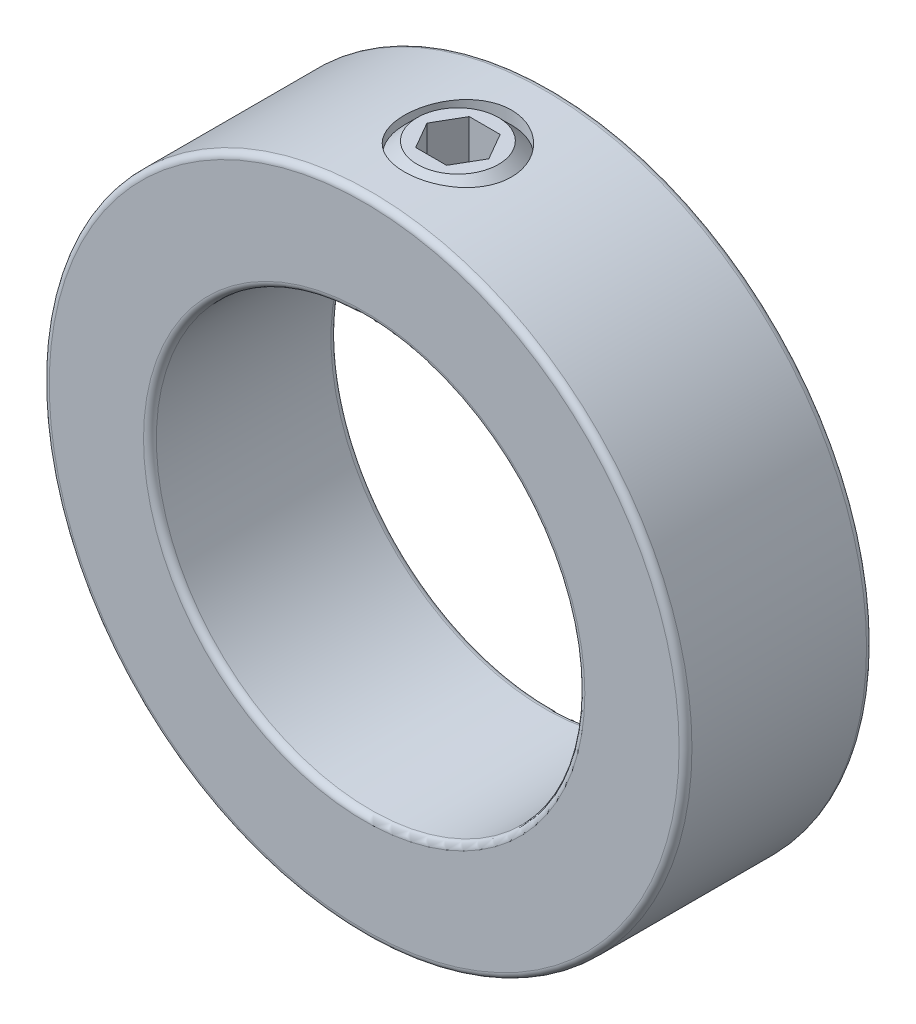
SolidWorks part; units mm, degrees
ref_plane "Front Plane" through (0, 0, 0) normal (0, 0, 1) x (1, 0, 0)
ref_plane "Top Plane" through (0, 0, 0) normal (0, 1, 0) x (1, 0, 0)
ref_plane "Right Plane" through (0, 0, 0) normal (1, 0, 0) x (0, 0, -1)
sketch "Sketch1" plane through (0, 0, 0) normal (0, 0, 1) x (1, 0, 0)
  circle A0 centre (0, 0) radius 38.1
  circle A1 centre (0, 0) radius 25.4
  point P4 (38.1, 0)
  dimension "Bore Dia" = 50.8
  dimension "OD" = 76.2
extrude "Extrude1" add sketch "Sketch1" along normal mid plane 22.225
sketch "Sketch2" plane through (41.275, 0, 0) normal (0, -1, 0) x (0, 0, -1)
  line L0 (11.1125, -41.275) -> (-11.1125, -41.275) construction
  line L1 (-11.1125, -3.175) -> (-11.1125, -79.375) construction
  line L2 (11.1125, -79.375) -> (11.1125, -3.175) construction
  circle A0 centre (0, -41.275) radius 6.35
  point P7 (0, -47.625)
  dimension "Set Screw Dia" = 12.7
extrude "Cut-Extrude1" cut sketch "Sketch2" against normal through all
fillet "Fillet1" radius 0.762 4 edges at (25.4, 0, -11.1125) (25.4, 0, 11.1125) (38.1, 0, -11.1125) (38.1, 0, 11.1125)
sketch "Sketch3" plane through (0, 0, 0) normal (0, 0, 1) x (1, 0, 0)
  line L0 (-4.8164, 25.4) -> (-1.8403, 25.4)
  line L1 (0, 27.2403) -> (-1.8403, 25.4)
  line L2 (0, 27.2403) -> (0, 38.1)
  line L3 (0, 38.1) -> (-4.8164, 38.1)
  line L4 (-6.35, 26.9336) -> (-6.35, 36.5664)
  line L5 (0, 25.4) -> (0, 0) construction
  line L6 (-6.35, 26.9336) -> (-6.35, 25.4) construction
  line L7 (-6.35, 25.4) -> (-4.8164, 25.4) construction
  line L8 (-6.35, 36.5664) -> (-6.35, 38.1) construction
  line L9 (-4.8164, 25.4) -> (-6.35, 26.9336)
  line L10 (-6.35, 36.5664) -> (-4.8164, 38.1)
  line L11 (-6.35, 38.1) -> (-4.8164, 38.1) construction
  line L12 (-1.8403, 25.4) -> (0, 25.4) construction
  line L13 (0, 25.4) -> (0, 27.2403) construction
  circle A1 centre (0, 0) radius 25.4 construction
  dimension "Screw Length" = 12.7
  dimension "D2" = 1.5336
  dimension "D1" = 1.8403
revolve "Revolve1" add sketch "Sketch3" angle 360 about L5
sketch "Sketch4" plane through (3.3734, 38.1, 0) normal (0, -1, 0) x (0, 0, -1)
  line L1 (0, 0.2927) -> (-3.175, -1.5404)
  line L2 (-3.175, -1.5404) -> (-3.175, -5.2065)
  line L3 (-3.175, -5.2065) -> (0, -7.0396)
  line L4 (0, -7.0396) -> (3.175, -5.2065)
  line L5 (3.175, -5.2065) -> (3.175, -1.5404)
  line L6 (3.175, -1.5404) -> (0, 0.2927)
  circle A0 centre (0, -3.3734) radius 3.175 construction
  circle A1 centre (0, -3.3734) radius 3.6662 construction
  dimension "D1" = 7.3323
  dimension "Hex Size" = 6.35
extrude "Cut-Extrude2" cut sketch "Sketch4" along normal blind 6.35
equation "\"D1@Fillet1\" = \"OD@Sketch1\"*.01"
equation "\"D1@Cut-Extrude2\" = \"Hex Size@Sketch4\""
equation "\"D2@Sketch3\" =(\"Set Screw Dia@Sketch2\"-\"D1@Sketch4\")/3.5"
equation "\"D1@Sketch3\" = \"D2@Sketch3\"*1.2"
